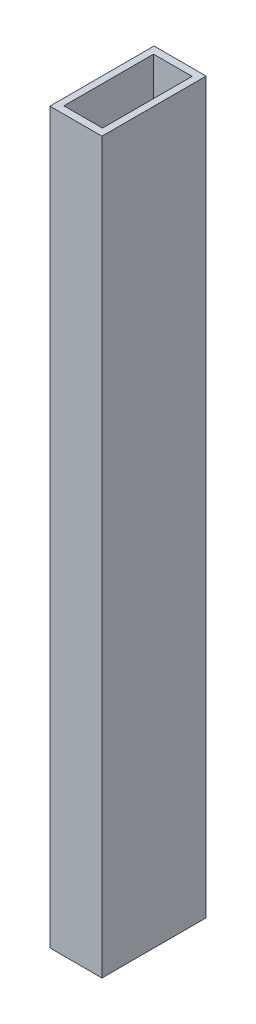
SolidWorks part; units mm, degrees
ref_plane "Front Plane" through (0, 0, 0) normal (0, 0, 1) x (1, 0, 0)
ref_plane "Top Plane" through (0, 0, 0) normal (0, 1, 0) x (1, 0, 0)
ref_plane "Right Plane" through (0, 0, 0) normal (1, 0, 0) x (0, 0, -1)
sketch "Sketch1" plane through (0, 0, 0) normal (0, 1, 0) x (1, 0, 0)
  line L0 (0, 0) -> (12.7, 0)
  line L1 (12.7, 0) -> (12.7, 25.4)
  line L3 (11.049, 23.622) -> (11.049, 1.778)
  line L4 (11.049, 1.778) -> (1.651, 1.778)
  line L5 (1.651, 1.778) -> (1.651, 23.622)
  line L7 (0, 25.4) -> (0, 0)
  line L8 (0, 25.4) -> (12.7, 25.4)
  line L9 (1.651, 23.622) -> (11.049, 23.622)
  dimension "D2" = 12.7
  dimension "D3" = 25.4
  dimension "D4" = 1.778
  dimension "D1" = 1.778
  dimension "D5" = 1.651
  dimension "D6" = 1.651
extrude "Boss-Extrude1" add sketch "Sketch1" along normal blind 177.8
equation "\"D4@Sketch1\"=\"D1@Sketch1\""
